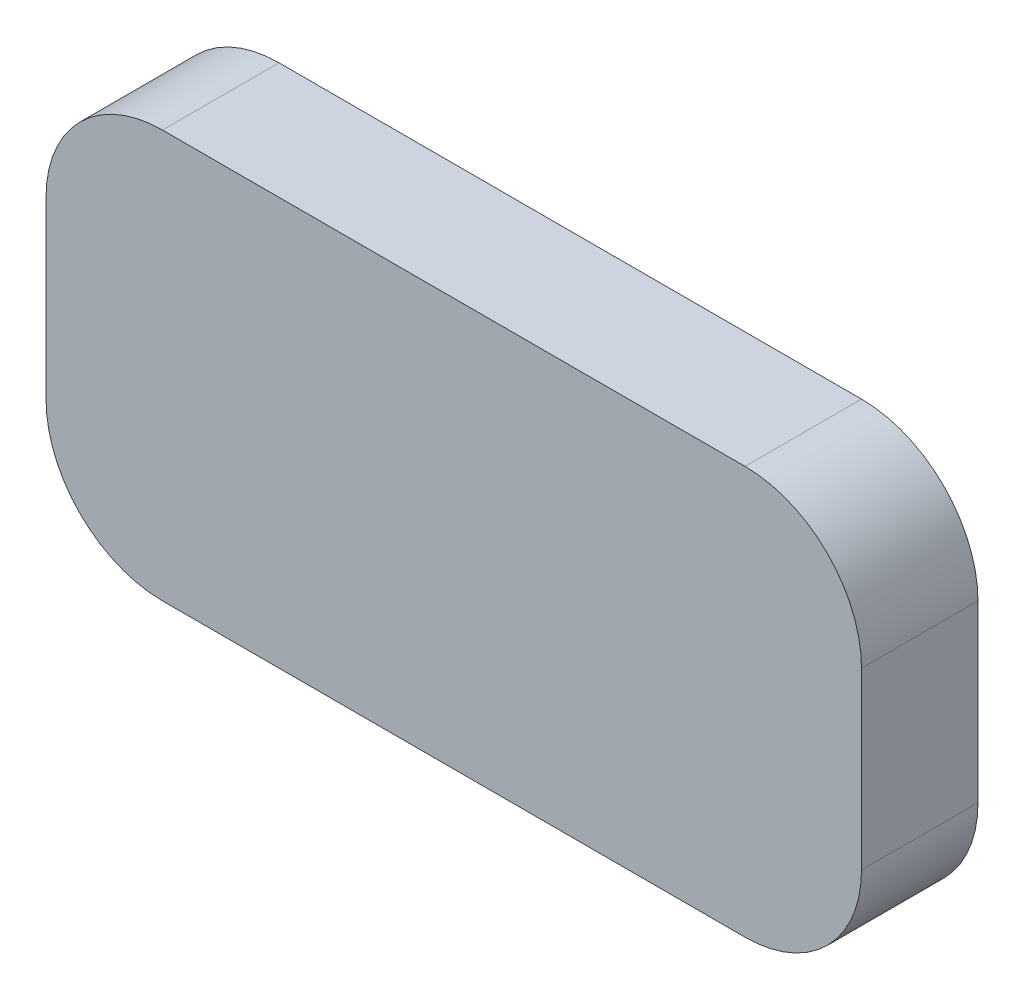
SolidWorks part; units mm, degrees
ref_plane "Спереди" through (0, 0, 0) normal (0, 0, 1) x (1, 0, 0)
ref_plane "Сверху" through (0, 0, 0) normal (0, 1, 0) x (1, 0, 0)
ref_plane "Справа" through (0, 0, 0) normal (1, 0, 0) x (0, 0, -1)
sketch "Эскиз1" plane through (0, 0, 0) normal (0, 0, 1) x (1, 0, 0)
  line L1 (-7, 3.5) -> (7, 3.5)
  line L2 (-7, 3.5) -> (-7, -3.5)
  line L3 (-7, -3.5) -> (7, -3.5)
  line L4 (7, 3.5) -> (7, -3.5)
  line L5 (-7, 3.5) -> (7, -3.5) construction
  line L6 (-7, -3.5) -> (7, 3.5) construction
  point P0 (0, 0)
  dimension "D1" = 7
  dimension "D2" = 14
extrude "Бобышка-Вытянуть1" add sketch "Эскиз1" along normal blind 2
fillet "Скругление1" radius 2 4 edges at (-7, -3.5, 1) (-7, 3.5, 1) (7, -3.5, 1) (7, 3.5, 1)
